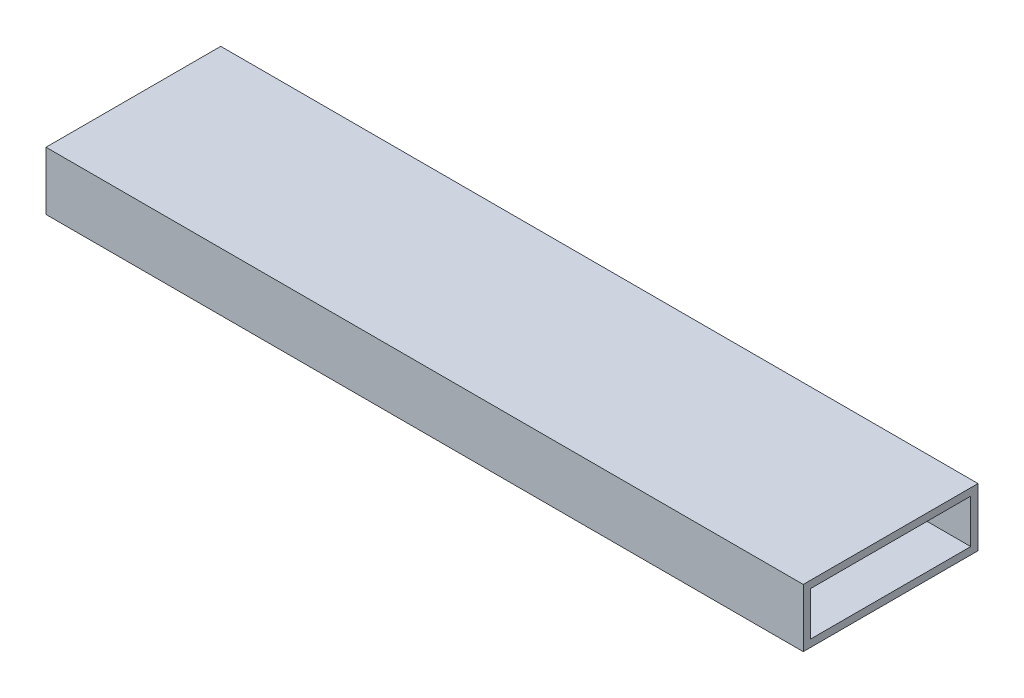
SolidWorks part; units mm, degrees
ref_plane "Front Plane" through (0, 0, 0) normal (0, 0, 1) x (1, 0, 0)
ref_plane "Top Plane" through (0, 0, 0) normal (0, 1, 0) x (1, 0, 0)
ref_plane "Right Plane" through (0, 0, 0) normal (1, 0, 0) x (0, 0, -1)
sketch "Sketch1" plane through (0, 0, 0) normal (1, 0, 0) x (0, 0, -1)
  line L1 (-2.0328, -6.0498) -> (74.1672, -6.0498)
  line L2 (-2.0328, -6.0498) -> (-2.0328, 19.3502)
  line L3 (-2.0328, 19.3502) -> (74.1672, 19.3502)
  line L4 (74.1672, -6.0498) -> (74.1672, 19.3502)
  dimension "D1" = 76.2
  dimension "D2" = 25.4
extrude "Boss-Extrude1" add sketch "Sketch1" along normal blind 330.2
sketch "Sketch2" plane through (0, 0, 0) normal (-1, 0, 0) x (0, 0, 1)
  line L0 (-74.1672, -6.0498) -> (-74.1672, 19.3502) construction
  line L1 (-70.9922, -2.8748) -> (-1.1422, -2.8748)
  line L2 (-70.9922, -2.8748) -> (-70.9922, 16.1752)
  line L3 (-70.9922, 16.1752) -> (-1.1422, 16.1752)
  line L4 (-1.1422, -2.8748) -> (-1.1422, 16.1752)
  line L5 (2.0328, 19.3502) -> (2.0328, -6.0498) construction
  line L6 (-74.1672, 19.3502) -> (2.0328, 19.3502) construction
  line L7 (2.0328, -6.0498) -> (-74.1672, -6.0498) construction
  dimension "D1" = 3.175
  dimension "D2" = 3.175
  dimension "D3" = 3.175
  dimension "D4" = 3.175
extrude "Cut-Extrude1" cut sketch "Sketch2" against normal through all
